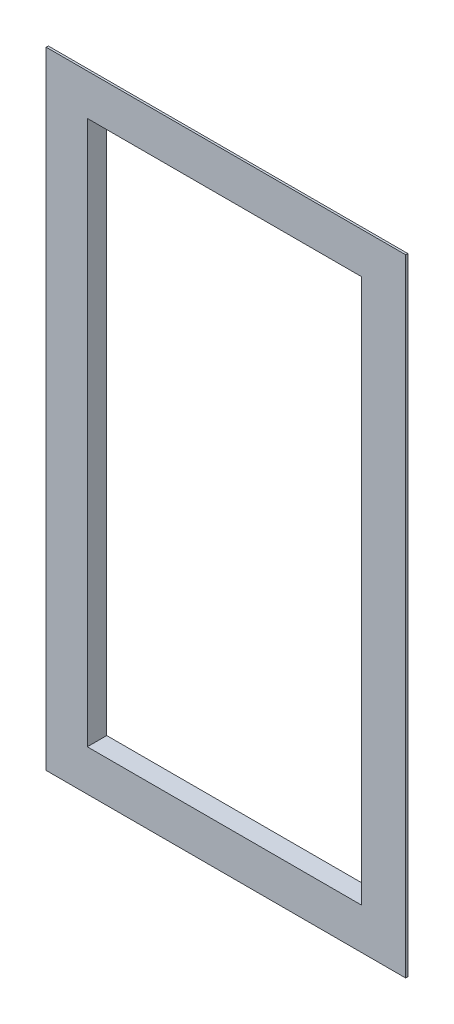
SolidWorks part; units mm, degrees
ref_plane "Front Plane" through (0, 0, 0) normal (0, 0, 1) x (1, 0, 0)
ref_plane "Top Plane" through (0, 0, 0) normal (0, 1, 0) x (1, 0, 0)
ref_plane "Right Plane" through (0, 0, 0) normal (1, 0, 0) x (0, 0, -1)
sketch "Sketch1" plane through (0, 0, 0) normal (0, 0, 1) x (1, 0, 0)
  line L2 (15.8705, 137.4127) -> (-48.8465, 137.4127)
  line L5 (-41.4503, 32.0164) -> (-48.8465, 24.6202)
  line L7 (7.9626, 32.0164) -> (7.9626, 130.0164)
  line L8 (-41.4503, 130.0164) -> (7.9626, 130.0164)
  line L9 (-41.4503, 32.0164) -> (-41.4503, 130.0164)
  line L10 (-48.8465, 24.6202) -> (15.8705, 24.6202)
  line L13 (-41.4503, 32.0164) -> (7.9626, 32.0164)
  line L14 (-48.8465, 137.4127) -> (-48.8465, 24.6202)
  line L15 (15.8705, 137.4127) -> (15.8705, 24.6202)
  line L16 (7.9626, 32.0164) -> (15.8705, 24.6202)
  line L17 (15.8705, 137.4127) -> (7.9626, 130.0164)
  line L18 (-48.8465, 137.4127) -> (-41.4503, 130.0164)
  dimension "D1" = 98
extrude "Boss-Extrude1" add sketch "Sketch1" along normal blind 3.5 contours L16 L13 L5 L10 | L18 L14 L5 L9 | L2 L18 L8 L17 | L15 L17 L7 L16
chamfer "Chamfer1" distance 7 angle 24 4 edges at (15.8705, 81.0164, 0) (-16.488, 137.4127, 0) (-48.8465, 81.0164, 0) (-16.488, 24.6202, 0)
